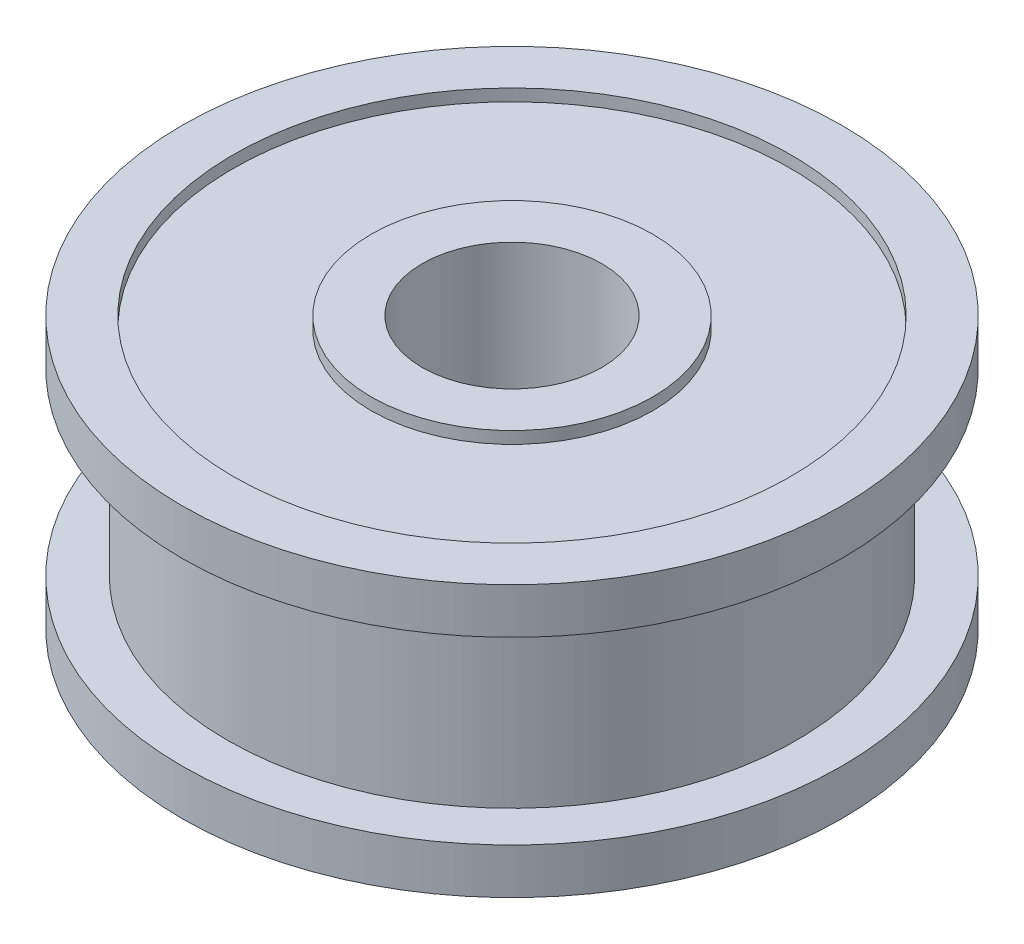
SolidWorks part; units mm, degrees
material "1060 Alloy"
ref_plane "Front Plane" through (0, 0, 0) normal (0, 0, 1) x (1, 0, 0)
ref_plane "Top Plane" through (0, 0, 0) normal (0, 1, 0) x (1, 0, 0)
ref_plane "Right Plane" through (0, 0, 0) normal (1, 0, 0) x (0, 0, -1)
sketch "Sketch1" plane through (0, 0, 0) normal (0, 1, 0) x (1, 0, 0)
  circle A0 centre (0, 0) radius 5.5
  dimension "D1" = 11
extrude "Boss-Extrude1" add sketch "Sketch1" along normal blind 0.76
sketch "Sketch2" plane through (0, 0.76, 0) normal (0, 1, 0) x (1, 0, 0)
  circle A0 centre (0, 0) radius 4.75
  dimension "D1" = 9.5
extrude "Boss-Extrude2" add sketch "Sketch2" along normal blind 3
sketch "Sketch3" plane through (0, 3.76, 0) normal (0, 1, 0) x (1, 0, 0)
  circle A0 centre (0, 0) radius 5.5
  dimension "D1" = 11
extrude "Boss-Extrude3" add sketch "Sketch3" along normal blind 0.76
sketch "Sketch4" plane through (0, 0, 0) normal (0, -1, 0) x (1, 0, 0)
  circle A0 centre (0, 0) radius 1.5
  dimension "D1" = 3
extrude "Cut-Extrude1" cut sketch "Sketch4" along direction (0, 1, 0) on the side against the normal up to surface (4.52 mm away)
sketch "Sketch5" plane through (0, 4.52, 0) normal (0, 1, 0) x (1, 0, 0)
  circle A0 centre (0, 0) radius 4.65
  circle A1 centre (0, 0) radius 2.35
  circle A2 centre (0, 0) radius 1.5 construction
  dimension "D1" = 9.3
  dimension "D2" = 0.85
extrude "Cut-Extrude2" cut sketch "Sketch5" against normal blind 0.2
sketch "Sketch6" plane through (0, 0, 0) normal (0, -1, 0) x (1, 0, 0)
  circle A0 centre (0, 0) radius 4.65
  circle A1 centre (0, 0) radius 2.35
  circle A2 centre (0, 0) radius 1.5 construction
  dimension "D1" = 9.3
  dimension "D2" = 0.85
extrude "Cut-Extrude3" cut sketch "Sketch6" against normal blind 0.2
